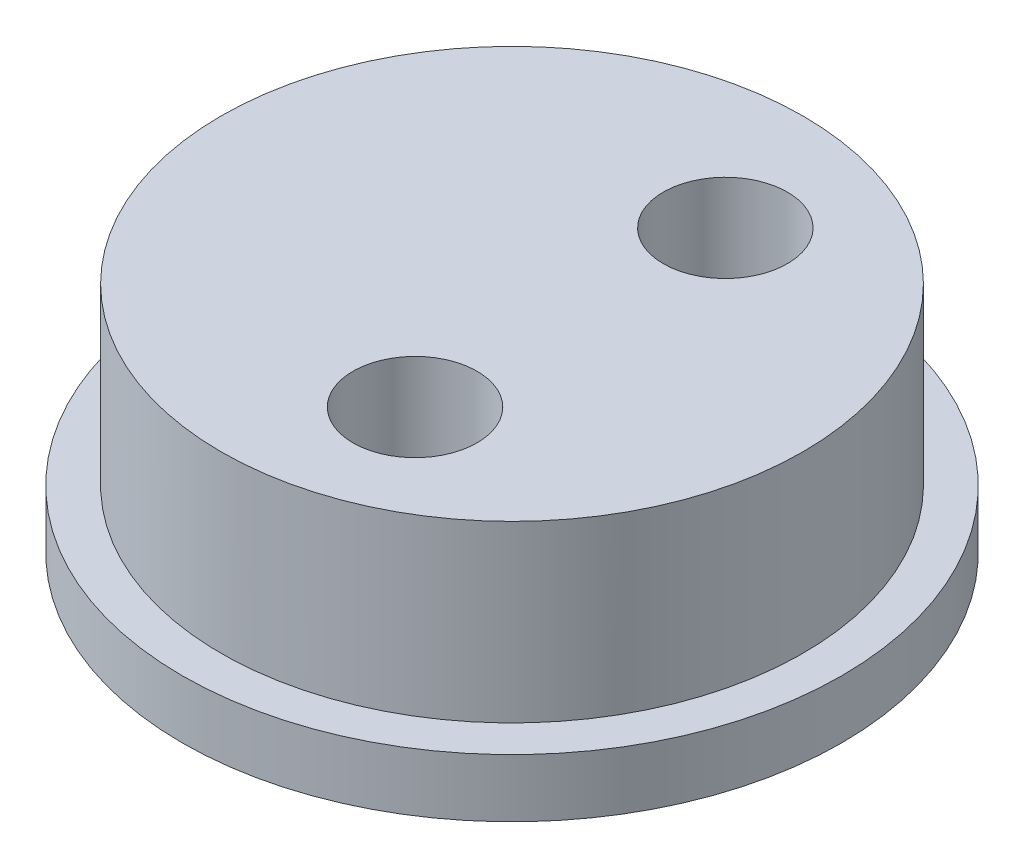
SolidWorks part; units mm, degrees
ref_plane "Front Plane" through (0, 0, 0) normal (0, 0, 1) x (1, 0, 0)
ref_plane "Top Plane" through (0, 0, 0) normal (0, 1, 0) x (1, 0, 0)
ref_plane "Right Plane" through (0, 0, 0) normal (1, 0, 0) x (0, 0, -1)
sketch "Sketch1" plane through (0, 0, 0) normal (0, 1, 0) x (1, 0, 0)
  line L0 (0, 0) -> (-1.5, 0) construction
  circle A1 centre (-1.5, 0) radius 7.5
  point P12 (0, 0)
  dimension "D3" = 15
  dimension "D2" = 1.5
extrude "Boss-Extrude1" add sketch "Sketch1" along normal blind 6
sketch "Sketch2" plane through (0, 0, 0) normal (0, -1, 0) x (1, 0, 0)
  line L0 (-12.8187, 0) -> (7.6603, 0) construction
  circle A0 centre (-1.5, 0) radius 8.5
  dimension "D2" = 17
  dimension "D1" = 1.5
extrude "Boss-Extrude2" add sketch "Sketch2" against normal blind 1.5
sketch "Sketch4" plane through (0, 6, 0) normal (0, 1, 0) x (1, 0, 0)
  line L0 (0, 8.8969) -> (0, -8.7328) construction
  circle A0 centre (0, 0) radius 4 construction
  circle A1 centre (0, 4) radius 1.6
  circle A2 centre (0, -4) radius 1.6
  dimension "D1" = 8
  dimension "D2" = 3.2
extrude "Cut-Extrude1" cut sketch "Sketch4" against normal through all
